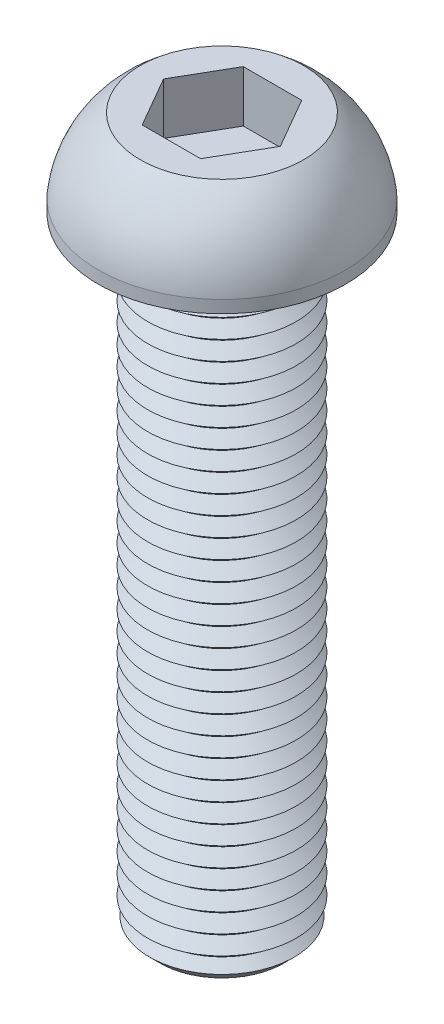
SolidWorks part; units mm, degrees
ref_plane "前视基准面" through (0, 0, 0) normal (0, 0, 1) x (1, 0, 0)
ref_plane "上视基准面" through (0, 0, 0) normal (0, 1, 0) x (1, 0, 0)
ref_plane "右视基准面" through (0, 0, 0) normal (1, 0, 0) x (0, 0, -1)
sketch "草图1" plane through (0, 0, 0) normal (0, 0, 1) x (1, 0, 0)
  line B0 (2.5, 0) -> (0, 0)
  line B1 (2.9164, 0.4164) -> (2.5, 0)
  line B2 (0, 0) -> (0, 28.5)
  line B3 (5, 25) -> (5, 25.5)
  line B4 (5, 25) -> (3, 25)
  line B5 (3.3, 28.5) -> (0, 28.5)
  line B6 (3, 25) -> (2.5, 24.6149)
  line B7 (3, 24.2297) -> (2.5, 24.6149)
  line B8 (3, 24.2297) -> (2.5, 23.8446)
  line B9 (3, 23.4595) -> (2.5, 23.8446)
  line B10 (3, 23.4595) -> (2.5, 23.0744)
  line B11 (3, 22.6892) -> (2.5, 23.0744)
  line B12 (3, 22.6892) -> (2.5, 22.3041)
  line B13 (3, 21.919) -> (2.5, 22.3041)
  line B14 (3, 21.919) -> (2.5, 21.5339)
  line B15 (3, 21.1487) -> (2.5, 21.5339)
  line B16 (3, 21.1487) -> (2.5, 20.7636)
  line B17 (3, 20.3785) -> (2.5, 20.7636)
  line B18 (3, 20.3785) -> (2.5, 19.9934)
  line B19 (3, 19.6082) -> (2.5, 19.9934)
  line B20 (3, 19.6082) -> (2.5, 19.2231)
  line B21 (3, 18.838) -> (2.5, 19.2231)
  line B22 (3, 18.838) -> (2.5, 18.4529)
  line B23 (3, 18.0677) -> (2.5, 18.4529)
  line B24 (3, 18.0677) -> (2.5, 17.6826)
  line B25 (3, 17.2975) -> (2.5, 17.6826)
  line B26 (3, 17.2975) -> (2.5, 16.9124)
  line B27 (3, 16.5272) -> (2.5, 16.9124)
  line B28 (3, 16.5272) -> (2.5, 16.1421)
  line B29 (3, 15.757) -> (2.5, 16.1421)
  line B30 (3, 15.757) -> (2.5, 15.3719)
  line B31 (3, 14.9867) -> (2.5, 15.3719)
  line B32 (3, 14.9867) -> (2.5, 14.6016)
  line B33 (3, 14.2165) -> (2.5, 14.6016)
  line B34 (3, 14.2165) -> (2.5, 13.8314)
  line B35 (3, 13.4462) -> (2.5, 13.8314)
  line B36 (3, 13.4462) -> (2.5, 13.0611)
  line B37 (3, 12.676) -> (2.5, 13.0611)
  line B38 (3, 12.676) -> (2.5, 12.2909)
  line B39 (3, 11.9057) -> (2.5, 12.2909)
  line B40 (3, 11.9057) -> (2.5, 11.5206)
  line B41 (3, 11.1355) -> (2.5, 11.5206)
  line B42 (3, 11.1355) -> (2.5, 10.7504)
  line B43 (3, 10.3652) -> (2.5, 10.7504)
  line B44 (3, 10.3652) -> (2.5, 9.9801)
  line B45 (3, 9.595) -> (2.5, 9.9801)
  line B46 (3, 9.595) -> (2.5, 9.2099)
  line B47 (3, 8.8247) -> (2.5, 9.2099)
  line B48 (3, 8.8247) -> (2.5, 8.4396)
  line B49 (3, 8.0545) -> (2.5, 8.4396)
  line B50 (3, 8.0545) -> (2.5, 7.6694)
  line B51 (3, 7.2842) -> (2.5, 7.6694)
  line B52 (3, 7.2842) -> (2.5, 6.8991)
  line B53 (3, 6.514) -> (2.5, 6.8991)
  line B54 (3, 6.514) -> (2.5, 6.1289)
  line B55 (3, 5.7437) -> (2.5, 6.1289)
  line B56 (3, 5.7437) -> (2.5, 5.3586)
  line B57 (3, 4.9735) -> (2.5, 5.3586)
  line B58 (3, 4.9735) -> (2.5, 4.5884)
  line B59 (3, 4.2032) -> (2.5, 4.5884)
  line B60 (3, 4.2032) -> (2.5, 3.8181)
  line B61 (3, 3.433) -> (2.5, 3.8181)
  line B62 (3, 3.433) -> (2.5, 3.0479)
  line B63 (3, 2.6627) -> (2.5, 3.0479)
  line B64 (3, 2.6627) -> (2.5, 2.2776)
  line B65 (3, 1.8925) -> (2.5, 2.2776)
  line B66 (3, 1.8925) -> (2.5, 1.5074)
  line B67 (3, 1.1222) -> (2.5, 1.5074)
  line B68 (3, 1.1222) -> (2.5, 0.7371)
  line B69 (2.9164, 0.4164) -> (2.5, 0.7371)
  arc B70 (5, 25.5) -> (3.3, 28.5) centre (0.7535, 25.0753) ccw
sketch_block_instance "A$C0879642A-1"
sketch_block "A$C0879642A"
revolve "旋转1" add sketch "草图1" angle 360 about L2
sketch "草图3" plane through (0, 28.5, 0) normal (0, 1, 0) x (1, 0, 0)
  line L1 (2.3579, 0) -> (1.1789, 2.042)
  line L2 (1.1789, 2.042) -> (-1.1789, 2.042)
  line L3 (-1.1789, 2.042) -> (-2.3579, 0)
  line L4 (-2.3579, 0) -> (-1.1789, -2.042)
  line L5 (-1.1789, -2.042) -> (1.1789, -2.042)
  line L6 (1.1789, -2.042) -> (2.3579, 0)
  circle A0 centre (0, 0) radius 2.042 construction
extrude "切除-拉伸1" cut sketch "草图3" against normal blind 2.08
